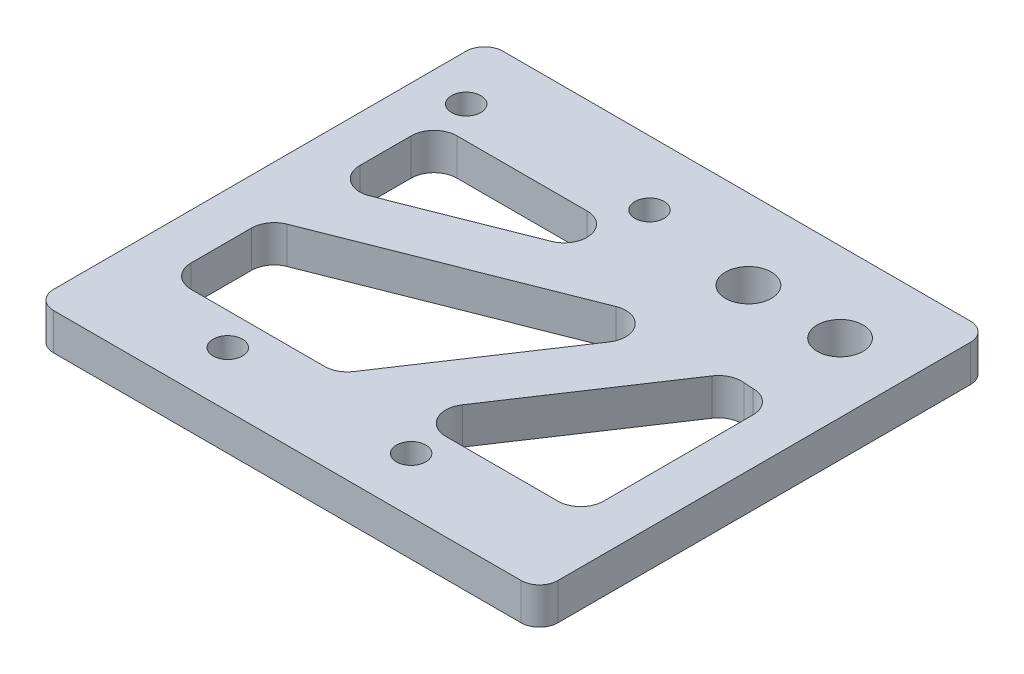
SolidWorks part; units mm, degrees
material "Thornel Mat VMA"
ref_plane "前视基准面" through (0, 0, 0) normal (0, 0, 1) x (1, 0, 0)
ref_plane "上视基准面" through (0, 0, 0) normal (0, 1, 0) x (1, 0, 0)
ref_plane "右视基准面" through (0, 0, 0) normal (1, 0, 0) x (0, 0, -1)
other "Configuration Table"
sketch "草图1" plane through (0, 0, 0) normal (0, 1, 0) x (1, 0, 0)
  line L1 (-20, 24.5) -> (20, 24.5)
  line L2 (-20, 24.5) -> (-20, -24.5)
  line L3 (-20, -24.5) -> (20, -24.5)
  line L4 (20, 24.5) -> (20, -24.5)
  line L5 (-20, 24.5) -> (20, -24.5) construction
  line L6 (-20, -24.5) -> (20, 24.5) construction
  point P0 (0, 0)
  dimension "D1" = 49
  dimension "D2" = 40
extrude "凸台-拉伸1" add sketch "草图1" along normal blind 4
sketch "草图3" plane through (0, 4, 0) normal (0, 1, 0) x (1, 0, 0)
  line L0 (-20, -24.5) -> (20, -24.5) construction
  line L1 (20, -24.5) -> (20, 24.5) construction
  line L2 (20, 24.5) -> (-20, 24.5) construction
  line L3 (-20, 24.5) -> (-20, -24.5) construction
  circle A0 centre (-5, -18.5) radius 1.6
  circle A1 centre (15, -18.5) radius 1.6
  circle A2 centre (-15, 17.5) radius 1.6
  circle A3 centre (5, 17.5) radius 1.6
  dimension "D1" = 3.2
  dimension "D2" = 20
  dimension "D3" = 20
  dimension "D4" = 6
  dimension "D5" = 5
  dimension "D6" = 7
  dimension "D7" = 5
extrude "切除-拉伸1" cut sketch "草图3" against normal blind 4
sketch "草图5" plane through (0, 0, 0) normal (0, -1, 0) x (1, 0, 0)
  line L0 (-20, 24.5) -> (20, 24.5) construction
  line L1 (20, -24.5) -> (35, -24.5)
  line L2 (20, -24.5) -> (20, 24.5)
  line L3 (20, 24.5) -> (35, 24.5)
  line L4 (35, -24.5) -> (35, 24.5)
  line L6 (44, 3) -> (27.5, -15.7816) construction
  circle A1 centre (27.5, -15.7816) radius 2.5
  circle A2 centre (44, 3) radius 9 construction
  dimension "D1" = 5
  dimension "D3" = 18
  dimension "D2" = 15
  dimension "D4" = 7.5
  dimension "D5" = 25
  dimension "D6" = 27.5
extrude "凸台-拉伸2" add sketch "草图5" against normal blind 4
sketch "草图6" plane through (0, 0, 0) normal (0, -1, 0) x (1, 0, 0)
  line L0 (-20, -24.5) -> (-20, 24.5) construction
  line L1 (-15, 15) -> (30, 15)
  line L2 (-15, 15) -> (-15, -14)
  line L3 (-15, -14) -> (30, -14)
  line L4 (30, 15) -> (30, -14)
  line L5 (35, -24.5) -> (35, 24.5) construction
  line L6 (27.5, -6.2816) -> (30, -6.2816) construction
  circle A0 centre (27.5, -15.7816) radius 9.5
  circle A1 centre (5, -17.5) radius 3.5 construction
  circle A2 centre (-15, -17.5) radius 3.5 construction
  circle A3 centre (-5, 18.5) radius 3.5 construction
  dimension "D1" = 7
  dimension "D4" = 19
  dimension "D2" = 5
  dimension "D3" = 5
extrude "切除-拉伸2" cut sketch "草图6" against normal blind 10 contours A0 L6 L4 L1 L2 L3
sketch "草图8" plane through (0, 0, 0) normal (0, -1, 0) x (1, 0, 0)
  line L0 (27.5, -15.7816) -> (7, 15)
  line L1 (-15, 15) -> (30, 15) construction
  line L2 (27.5, -15.7816) -> (-12, 15) construction
  line L3 (27.5, -15.7816) -> (-15, 1)
  line L4 (-15, 15) -> (-15, -14) construction
  line L5 (-15, 1) -> (-17, 1.7897)
  line L6 (-12, 15) -> (-14.3663, 16.844) construction
  line L7 (7, 15) -> (5.668, 17)
  dimension "D1" = 23
  dimension "D2" = 15
  dimension "D3" = 3
  dimension "D4" = 2
  dimension "D5" = 2
  dimension "D6" = 3
extrude "拉伸-薄壁2" add sketch "草图8" against normal blind 4 thin thin type mid plane wall 6
sketch "草图10" plane through (0, 0, 0) normal (0, -1, 0) x (1, 0, 0)
  line L0 (35.3049, -22.0889) -> (35, -21.9685)
  line L1 (35, -21.9685) -> (35, -21.631)
  line L2 (35, -21.631) -> (35.3049, -22.0889)
  circle A1 centre (27.5, -15.7816) radius 2.5
  dimension "D1" = 5
extrude "切除-拉伸4" cut sketch "草图10" against normal blind 4
fillet "圆角3" radius 2.5 11 edges at (19.6951, 2, -9.4744) (-15, 2, 4.2254) (-15, 2, 15) (3.3956, 2, 15) (-15, 2, -2.2254) (14.8195, 2, -14) (30, 2, 15) (30, 2, -6.6165) (25.0005, 2, -6.6164) (10.6044, 2, 15) (-15, 2, -14)
fillet "圆角4" radius 2 4 edges at (-20, 2, 24.5) (35, 2, -24.5) (35, 2, 24.5) (-20, 2, -24.5)
sketch "草图11" plane through (0, 0, 0) normal (0, -1, 0) x (1, 0, 0)
  circle A0 centre (17.5, -15.7816) radius 2.5
  circle A1 centre (27.5, -15.7816) radius 2.5 construction
  circle A2 centre (27.5, -15.7816) radius 2.5 construction
  dimension "D1" = 10
extrude "切除-拉伸5" cut sketch "草图11" against normal blind 10
